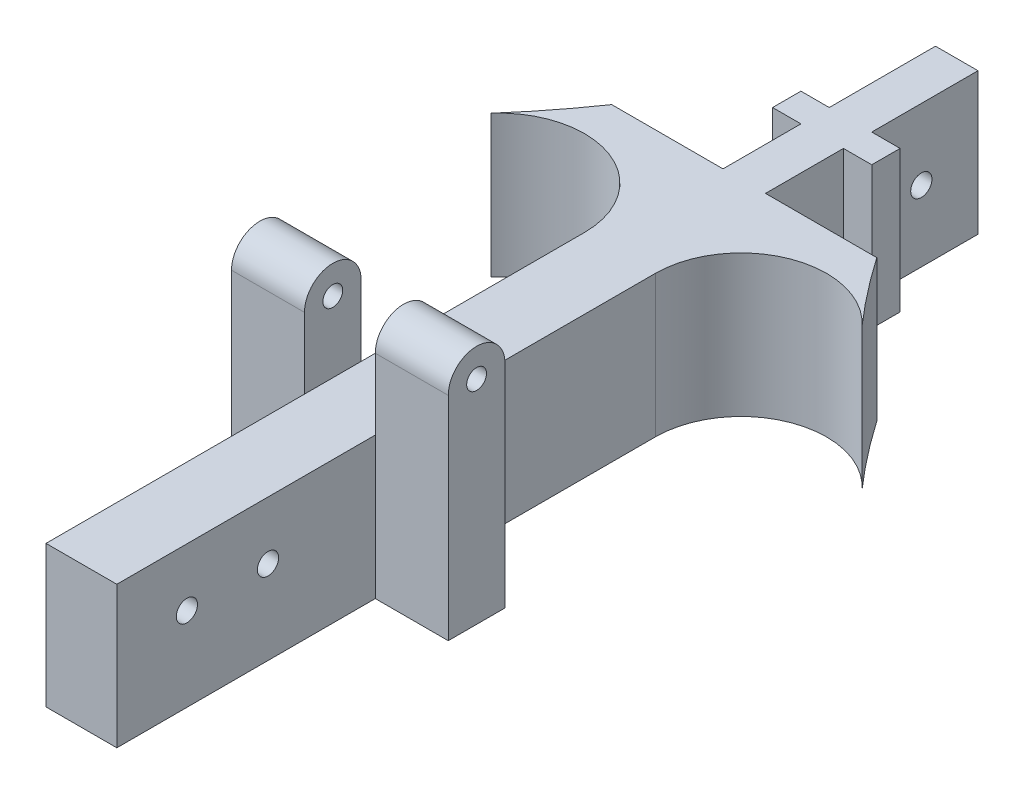
SolidWorks part; units mm, degrees
ref_plane "Plan de face" through (0, 0, 0) normal (0, 0, 1) x (1, 0, 0)
ref_plane "Plan de dessus" through (0, 0, 0) normal (0, 1, 0) x (1, 0, 0)
ref_plane "Plan de droite" through (0, 0, 0) normal (1, 0, 0) x (0, 0, -1)
sketch "Esquisse1" plane through (0, 0, 0) normal (0, 1, 0) x (1, 0, 0)
  line L0 (-3, 84.3983) -> (-3, 69.3983)
  line L1 (-3, 84.3983) -> (0, 84.3983)
  line L2 (-3, 65.3983) -> (-3, 54.3983)
  line L3 (-5, -39.1827) -> (0, -39.1827)
  line L4 (0, 84.3983) -> (0, -39.1827)
  line L5 (-3, 69.3983) -> (-7, 69.3983)
  line L6 (-3, 54.3983) -> (-18.71, 54.3983)
  line L7 (-3, 65.3983) -> (-7, 65.3983)
  line L8 (-7, 69.3983) -> (-7, 65.3983)
  line L9 (-5, 36.8425) -> (-5, -39.1827)
  arc A0 (-26.1833, 44.8157) -> (-18.71, 54.3983) centre (-105.5, 114.3795) ccw
  arc A1 (-5, 36.8425) -> (-26.1833, 44.8157) centre (-17.0922, 36.8425) ccw
  dimension "D7" = 211
  dimension "D1" = 3
  dimension "D2" = 4
  dimension "D3" = 4
  dimension "D4" = 15
  dimension "D5" = 11
  dimension "D6" = 15.71
extrude "Boss.-Extru.1" add sketch "Esquisse1" along normal blind 20
mirror "Symétrie1" about plane through (0, 20, -84.3983) normal (-1, 0, 0) of "Boss.-Extru.1"
sketch "Esquisse3" plane through (-3, 0, 0) normal (-1, 0, 0) x (0, 0, 1)
  line L2 (-84.3983, 20) -> (-69.3983, 20) construction
  line L3 (-65.3983, 20) -> (-54.3983, 20) construction
  line L4 (-84.3983, 20) -> (-84.3983, 0) construction
  circle A0 centre (-76.3983, 10) radius 1.5
  circle A1 centre (-60.3983, 10) radius 1.5
  dimension "D1" = 3
  dimension "D2" = 3
  dimension "D3" = 10
  dimension "D4" = 10
  dimension "D5" = 8
  dimension "D6" = 24
extrude "Enlèv. mat.-Extru.3" cut sketch "Esquisse3" against normal blind 20
sketch "Esquisse4" plane through (-5, 0, 0) normal (-1, 0, 0) x (0, 0, 1)
  circle A0 centre (29.292, 11.84) radius 1.5
extrude "Enlèv. mat.-Extru.4" cut sketch "Esquisse4" against normal blind 10
sketch "Esquisse5" plane through (-5, 0, 0) normal (-1, 0, 0) x (0, 0, 1)
  circle A0 centre (17.842, 11.84) radius 1.5
extrude "Enlèv. mat.-Extru.5" cut sketch "Esquisse5" against normal blind 10
sketch "Esquisse6" plane through (5, 0, 0) normal (1, 0, 0) x (0, 0, -1)
  line L0 (36.8425, 0) -> (-39.1827, 0) construction
  line L1 (5.3082, 0) -> (-2.6918, 0)
  line L2 (5.3082, 0) -> (5.3082, 30)
  line L4 (-2.6918, 0) -> (-2.6918, 30)
  arc A0 (-2.6918, 30) -> (5.3082, 30) centre (1.3082, 30) cw
  circle A1 centre (1.3082, 30) radius 1.4
  dimension "D2" = 30
  dimension "D1" = 8
ref_plane "Plan1" through (0, 0, 0) normal (-1, 0, 0) x (0, 0, 1)
extrude "Boss.-Extru.2" add sketch "Esquisse6" along normal blind 10.3
mirror "Symétrie2" about plane through (0, 0, 0) normal (-1, 0, 0) of "Boss.-Extru.2"
